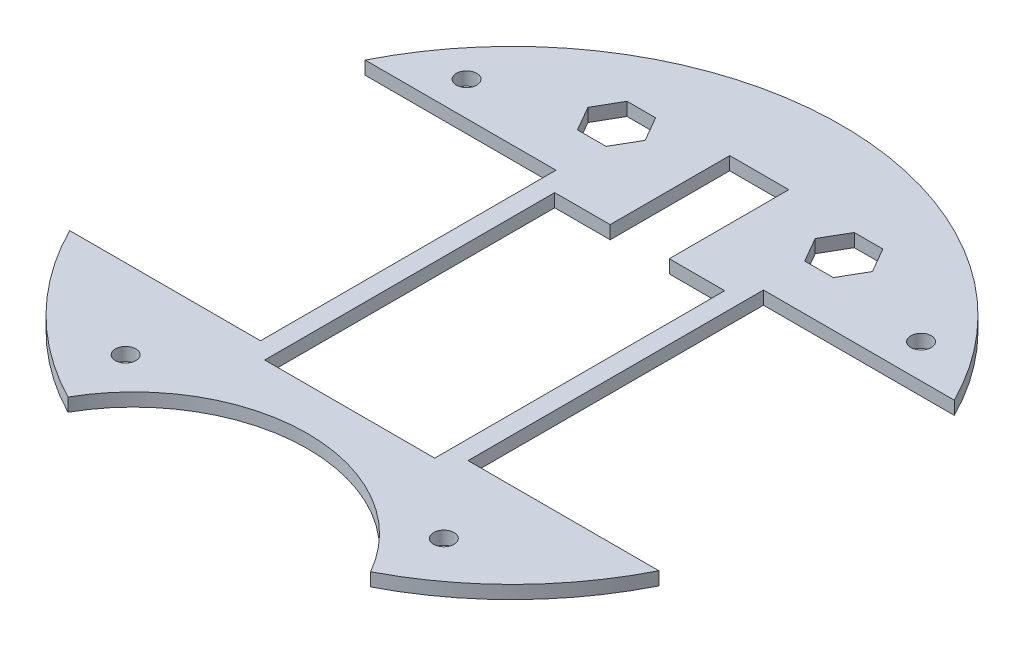
SolidWorks part; units mm, degrees
material "Acrylic (Medium-high impact)"
ref_plane "Front Plane" through (0, 0, 0) normal (0, 0, 1) x (1, 0, 0)
ref_plane "Top Plane" through (0, 0, 0) normal (0, 1, 0) x (1, 0, 0)
ref_plane "Right Plane" through (0, 0, 0) normal (1, 0, 0) x (0, 0, -1)
sketch "Sketch1" plane through (0, 0, 0) normal (0, 1, 0) x (1, 0, 0)
  line L0 (0, -83.2398) -> (-33.2911, -64.4046) construction
  line L1 (0, -83.2398) -> (0, 0) construction
  arc A0 (33.2911, -64.4046) -> (-33.2911, -64.4046) centre (0, 0) ccw
  arc A1 (33.2911, -64.4046) -> (-33.2911, -64.4046) centre (0, -83.2398) ccw
  dimension "D1" = 145
  dimension "D2" = 76.5
  dimension "D3" = 60.5
extrude "Boss-Extrude1" add sketch "Sketch1" along normal blind 2.9
sketch "solenoid placement" plane through (0, 2.9, 0) normal (0, 1, 0) x (1, 0, 0)
  line L4 (-18.7, -35.7) -> (18.7, -35.7)
  line L5 (18.7, -35.7) -> (18.7, 28.1)
  line L6 (18.7, 28.1) -> (-18.7, 28.1)
  line L7 (-18.7, 28.1) -> (-18.7, -35.7)
  line L8 (-18.7, -35.7) -> (18.7, -35.7)
  line L9 (18.7, -35.7) -> (18.7, 28.1)
  line L10 (18.7, 28.1) -> (-18.7, 28.1)
  line L11 (-18.7, 28.1) -> (-18.7, -35.7)
  circle A1 centre (0, 0) radius 72.5 construction
  arc A2 (33.2911, -64.4046) -> (-33.2911, -64.4046) centre (0, 0) ccw construction
  dimension "D1" = 0
extrude "Cut-Extrude1" cut sketch "solenoid placement" against normal through all
sketch "Sketch3" plane through (0, 2.9, 0) normal (0, 1, 0) x (1, 0, 0)
  line L4 (-34.63, -32.5) -> (-22.83, -32.5)
  line L5 (-22.83, -32.5) -> (-22.83, 32.5)
  line L6 (-22.83, 32.5) -> (-64.8074, 32.5)
  line L7 (-64.8074, -32.5) -> (-34.63, -32.5)
  line L8 (-34.63, -32.5) -> (-22.83, -32.5)
  line L9 (-22.83, -32.5) -> (-22.83, 32.5)
  line L10 (-22.83, 32.5) -> (-64.8074, 32.5)
  line L11 (-64.8074, -32.5) -> (-34.63, -32.5)
  line L12 (34.63, -32.5) -> (64.8074, -32.5)
  line L13 (64.8074, 32.5) -> (22.83, 32.5)
  line L14 (22.83, 32.5) -> (22.83, -32.5)
  line L15 (22.83, -32.5) -> (34.63, -32.5)
  line L16 (34.63, -32.5) -> (64.8074, -32.5)
  line L17 (64.8074, 32.5) -> (22.83, 32.5)
  line L18 (22.83, 32.5) -> (22.83, -32.5)
  line L19 (22.83, -32.5) -> (34.63, -32.5)
  arc A2 (-64.8074, 32.5) -> (-64.8074, -32.5) centre (0, 0) ccw
  arc A3 (-64.8074, 32.5) -> (-64.8074, -32.5) centre (0, 0) ccw
  arc A4 (64.8074, -32.5) -> (64.8074, 32.5) centre (0, 0) ccw
  arc A5 (64.8074, -32.5) -> (64.8074, 32.5) centre (0, 0) ccw
  dimension "D2" = 0
  dimension "D1" = 0
extrude "Cut-Extrude3" cut sketch "Sketch3" against normal through all
sketch "Sketch4" plane through (0, 2.9, 0) normal (0, 1, 0) x (1, 0, 0)
  line L0 (18.7, 28.1) -> (-18.7, 28.1) construction
  line L1 (-6.5, 28.1) -> (6.5, 28.1)
  line L2 (-6.5, 28.1) -> (-6.5, 54.4)
  line L3 (6.5, 54.4) -> (-6.5, 54.4) construction
  line L4 (6.5, 28.1) -> (6.5, 54.4)
  line L5 (6.5, 54.4) -> (-6.5, 54.4)
  point P6 (0, 28.1)
extrude "Cut-Extrude4" cut sketch "Sketch4" against normal through all
sketch "Sketch5" plane through (0, 2.9, 0) normal (0, 1, 0) x (1, 0, 0)
  line L0 (0, 0) -> (0, 72.5) construction
  line L1 (-18.7069, 48) -> (-21.8534, 53.45)
  line L2 (-21.8534, 53.45) -> (-28.1466, 53.45)
  line L3 (-28.1466, 53.45) -> (-31.2931, 48)
  line L4 (-31.2931, 48) -> (-28.1466, 42.55)
  line L5 (-28.1466, 42.55) -> (-21.8534, 42.55)
  line L6 (-21.8534, 42.55) -> (-18.7069, 48)
  line L7 (21.8534, 42.55) -> (18.7069, 48)
  line L8 (28.1466, 42.55) -> (21.8534, 42.55)
  line L9 (31.2931, 48) -> (28.1466, 42.55)
  line L10 (28.1466, 53.45) -> (31.2931, 48)
  line L11 (21.8534, 53.45) -> (28.1466, 53.45)
  line L12 (18.7069, 48) -> (21.8534, 53.45)
  circle A0 centre (-25, 48) radius 5.45 construction
  arc A1 (64.8074, 32.5) -> (-64.8074, 32.5) centre (0, 0) ccw construction
  circle A2 centre (25, 48) radius 5.45 construction
  dimension "D3" = 10.9
extrude "Cut-Extrude5" cut sketch "Sketch5" against normal through all
sketch "Sketch6" plane through (0, 2.9, 0) normal (0, 1, 0) x (1, 0, 0)
  circle A1 centre (35, -50) radius 2.25
  circle A2 centre (35, -50) radius 2.25
  circle A3 centre (-35, -50) radius 2.25
  circle A4 centre (-35, -50) radius 2.25
  circle A5 centre (-50, 40) radius 2.25
  circle A6 centre (-50, 40) radius 2.25
  circle A7 centre (50, 40) radius 2.25
  circle A8 centre (50, 40) radius 2.25
  dimension "D1" = 0
  dimension "D2" = 0
  dimension "D3" = 0
  dimension "D4" = 0
extrude "Cut-Extrude6" cut sketch "Sketch6" against normal through all
equation "\"smallPulleyTeeth\"= 15"
equation "\"largePulleyTeeth\"= 30"
equation "\"eighthThick\"= 2.9mm"
equation "\"sixteenthThick\" = 1.7mm"
equation "\"quarterThick\"=5.9mm"
equation "\"OD\" = 145mm"
equation "\"puckAngle\" = 60.5deg"
equation "\"D1@Sketch1\"=\"OD\""
equation "\"puckDiam\" = 76.5mm"
equation "\"D2@Sketch1\"=\"puckDiam\""
equation "\"D3@Sketch1\"=\"puckAngle\""
equation "\"D1@Boss-Extrude1\"=\"eighthThick\""
equation "\"axlePress\" = 5.9mm"
equation "\"press\" = 0.2mm"
equation "\"wheelClear\" = 0.3mm"
equation "\"10-32clear\" = 4.5mm"
equation "\"6-32clear\" = 3.3mm"
equation "\"8-32clear\" = 4.0mm"
equation "\"wheelHeight\" = 22mm"
equation "\"wheelWell\" = 65mm"
